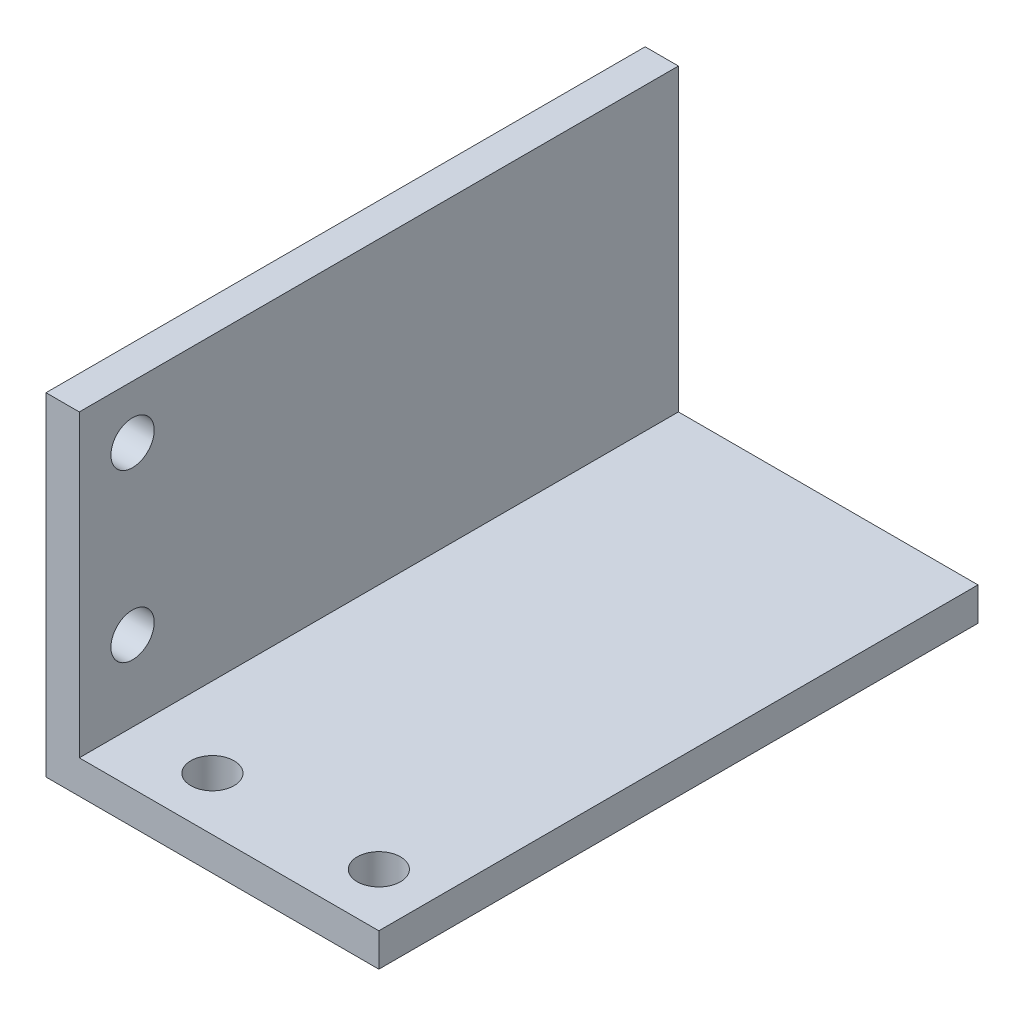
SolidWorks part; units mm, degrees
material "Lega 1060"
ref_plane "Piano frontale" through (0, 0, 0) normal (0, 0, 1) x (1, 0, 0)
ref_plane "Piano superiore" through (0, 0, 0) normal (0, 1, 0) x (1, 0, 0)
ref_plane "Piano destro" through (0, 0, 0) normal (1, 0, 0) x (0, 0, -1)
sketch "Schizzo1" plane through (0, 0, 0) normal (0, 0, 1) x (1, 0, 0)
  line L0 (0, 0) -> (0, 50)
  line L1 (0, 50) -> (5, 50)
  line L2 (5, 50) -> (5, 5)
  line L3 (5, 5) -> (50, 5)
  line L4 (50, 5) -> (50, 0)
  line L5 (50, 0) -> (0, 0)
  dimension "D1" = 5
  dimension "D2" = 5
  dimension "D3" = 50
  dimension "D4" = 50
extrude "Estrusione-Estrusione1" add sketch "Schizzo1" along normal blind 90
sketch "Schizzo2" plane through (0, 0, 0) normal (0, -1, 0) x (1, 0, 0)
  line L0 (5.4524, 82) -> (42.7933, 82) construction
  line L1 (0, 90) -> (50, 90) construction
  line L5 (50, 90) -> (50, 0) construction
  point P4 (17, 82)
  point P5 (42, 82)
  dimension "D1" = 8
  dimension "D2" = 25
  dimension "D3" = 8
sketch "Schizzo3" plane through (0, 0, 0) normal (-1, 0, 0) x (0, 0, 1)
  line L0 (82, 44.621) -> (82, 5.772) construction
  line L1 (90, 50) -> (90, 0) construction
  line L2 (90, 50) -> (0, 50) construction
  point P4 (82, 42)
  point P5 (82, 17)
  dimension "D1" = 8
  dimension "D2" = 8
  dimension "D3" = 25
hole_wizard "Foro Ø6.5 (6.5)-1" positions "Schizzo5" profile "Schizzo4" hole size "Ø6.5" standard "ISO" end condition through all
sketch "Schizzo5" plane through (0, 0, 0) normal (0, -1, 0) x (-1, 0, 0)
  point P0 (-17, -82)
  point P3 (-42, -82)
sketch "Schizzo4" plane through (17, 0, 82) normal (1, 0, 0) x (0, 0, -1)
  line L0 (0, 0) -> (0, 50)
  line L1 (0, 50) -> (3.25, 50)
  line L2 (3.25, 50) -> (3.25, 0)
  line L5 (3.25, 0) -> (0, 0)
  line L11 (0, -6.35) -> (0, 107.95) construction
  dimension "Thru Hole Dia." = 6.5
  dimension "Thru Hole Depth" = 50
hole_wizard "Foro Ø6.5 (6.5)-2" positions "Schizzo7" profile "Schizzo6" hole size "Ø6.5" standard "ISO"
sketch "Schizzo7" plane through (0, 0, 0) normal (-1, 0, 0) x (0, 0, 1)
  point P1 (82, 42)
  point P4 (82, 17)
sketch "Schizzo6" plane through (0, 42, 82) normal (0, 1, 0) x (0, 0, 1)
  line L0 (0, 0) -> (0, 6.9528)
  line L1 (0, 6.9528) -> (3.25, 5)
  line L2 (3.25, 5) -> (3.25, 0)
  line L5 (3.25, 0) -> (0, 0)
  line L10 (0, 6.9528) -> (-3.25, 5) construction
  line L11 (0, -6.35) -> (0, 107.95) construction
  dimension "Hole Dia." = 6.5
  dimension "Hole Depth" = 5
  dimension "Drill Angle" = 118
